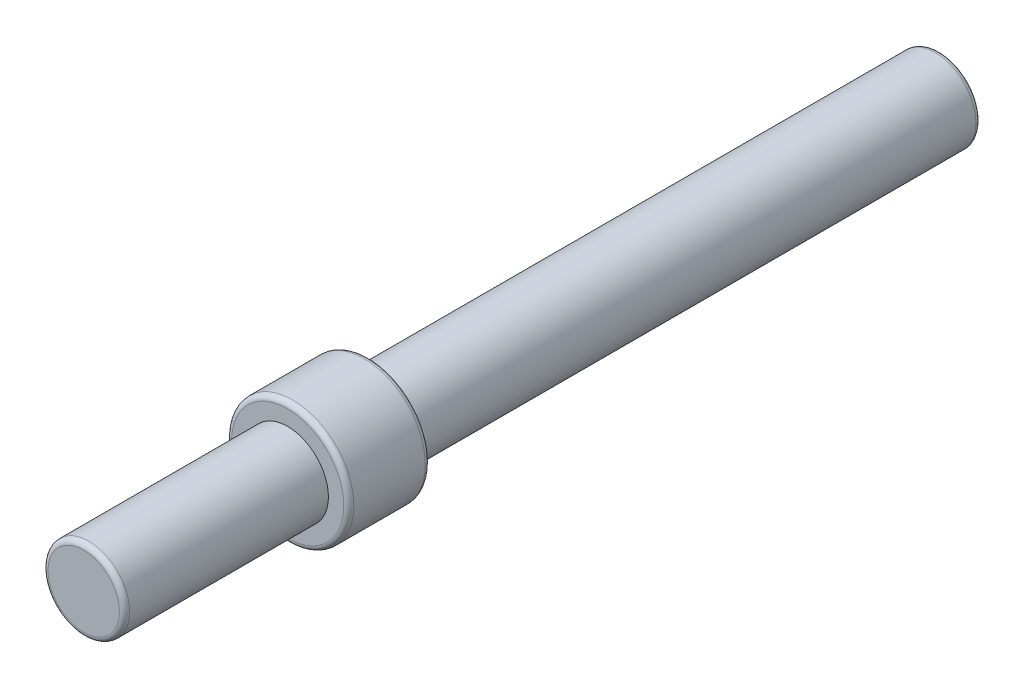
SolidWorks part; units mm, degrees
ref_plane "前视基准面" through (0, 0, 0) normal (0, 0, 1) x (1, 0, 0)
ref_plane "上视基准面" through (0, 0, 0) normal (0, 1, 0) x (1, 0, 0)
ref_plane "右视基准面" through (0, 0, 0) normal (1, 0, 0) x (0, 0, -1)
sketch "草图1" plane through (0, 0, 0) normal (0, 0, 1) x (1, 0, 0)
  circle A0 centre (0, 0) radius 4
  dimension "D1" = 8
extrude "凸台-拉伸1" add sketch "草图1" along normal blind 20
cosmetic thread "装饰螺纹线13" parameters "D1"=20, "D2"=7.8
cosmetic thread "装饰螺纹线14" parameters "D1"=20, "D2"=7.8
sketch "草图2" plane through (0, 0, 0) normal (0, 0, 1) x (1, 0, 0)
  circle A0 centre (0, 0) radius 6
  dimension "D1" = 12
extrude "凸台-拉伸2" add sketch "草图2" against normal blind 8
sketch "草图3" plane through (0, 0, -8) normal (0, 0, -1) x (-1, 0, 0)
  circle A0 centre (0, 0) radius 4
  dimension "D1" = 8
extrude "凸台-拉伸5" add sketch "草图3" along normal blind 56
fillet "圆角1" radius 0.5 1 edges at (4, 0, 20)
fillet "圆角2" radius 0.5 3 edges at (-4, 0, -64) (6, 0, -8) (6, 0, 0)
